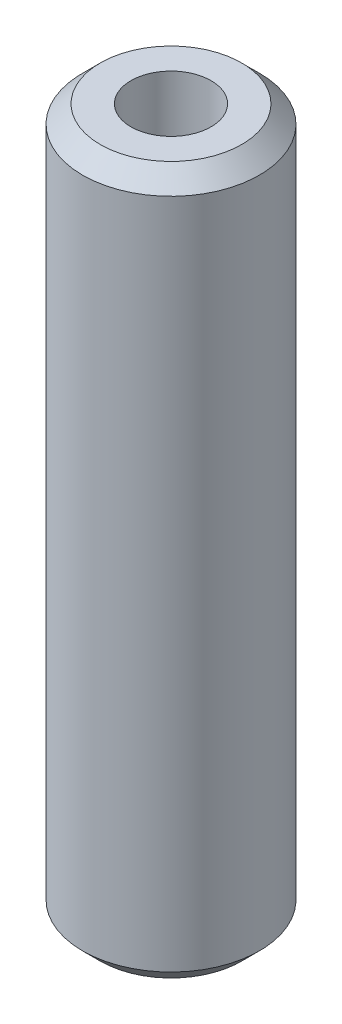
SolidWorks part; units mm, degrees
material "6061-T4 (SS)"
ref_plane "Front Plane" through (0, 0, 0) normal (0, 0, 1) x (1, 0, 0)
ref_plane "Top Plane" through (0, 0, 0) normal (0, 1, 0) x (1, 0, 0)
ref_plane "Right Plane" through (0, 0, 0) normal (1, 0, 0) x (0, 0, -1)
sketch "Sketch1" plane through (0, 0, 0) normal (0, 1, 0) x (1, 0, 0)
  circle A0 centre (0, 0) radius 12.7
  dimension "D1" = 25.4
extrude "Boss-Extrude1" add sketch "Sketch1" along normal blind 101.6
sketch "Sketch8" plane through (0, 101.6, 0) normal (0, 1, 0) x (1, 0, 0)
  line L0 (-17.7271, 0) -> (19.3287, 0) construction
  line L1 (0, 13.7715) -> (0, -14.2504) construction
hole_wizard "1/2-20 Tapped Hole1" positions "3DSketch6" profile "Sketch10" tap size "1/2-20" standard "ANSI Inch"
sketch3d "3DSketch6"
  line L0 (0, 101.6, -13.7715) -> (0, 101.6, 14.2504) construction
  line L1 (-17.7271, 101.6, 0) -> (19.3287, 101.6, 0) construction
  point P0 (0, 101.6, 0)
cosmetic thread "Hole Thread1" parameters "D1"=3.048, "D2"=12.7
sketch "Sketch10" plane through (0, 101.6, 0) normal (1, 0, 0) x (0, 0, 1)
  line L0 (0, 0) -> (0, 41.5576)
  line L1 (0, 41.5576) -> (5.7544, 38.1)
  line L2 (5.7544, 38.1) -> (5.7544, 0)
  line L5 (5.7544, 0) -> (0, 0)
  line L10 (0, 41.5576) -> (-5.7544, 38.1) construction
  line L11 (0, -6.35) -> (0, 107.95) construction
  dimension "Tap Drill Dia." = 11.5087
  dimension "Tap Drill Depth" = 38.1
  dimension "Drill Angle" = 118
sketch "Sketch13" plane through (0, 0, 0) normal (0, -1, 0) x (1, 0, 0)
  line L0 (-15.3181, 0) -> (17.1158, 0) construction
  line L1 (0, 13.5374) -> (0, -14.2613) construction
hole_wizard "1/2-20 Tapped Hole2" positions "3DSketch9" profile "Sketch14" tap size "1/2-20" standard "ANSI Inch"
sketch3d "3DSketch9"
  line L0 (0, 0, 13.5374) -> (0, 0, -14.2613) construction
  line L1 (-15.3181, 0, 0) -> (17.1158, 0, 0) construction
  point P0 (0, 0, 0)
sketch "Sketch14" plane through (0, 0, 0) normal (1, 0, 0) x (0, 0, -1)
  line L0 (0, 0) -> (0, 41.5576)
  line L1 (0, 41.5576) -> (5.7544, 38.1)
  line L2 (5.7544, 38.1) -> (5.7544, 0)
  line L5 (5.7544, 0) -> (0, 0)
  line L10 (0, 41.5576) -> (-5.7544, 38.1) construction
  line L11 (0, -6.35) -> (0, 107.95) construction
  dimension "Tap Drill Dia." = 11.5087
  dimension "Tap Drill Depth" = 38.1
  dimension "Drill Angle" = 118
cosmetic thread "Hole Thread2" parameters "D1"=3.048, "D2"=12.7
chamfer "Chamfer1" distance 2.54 angle 45 2 edges at (0, 101.6, 12.7) (0, 0, 12.7)
